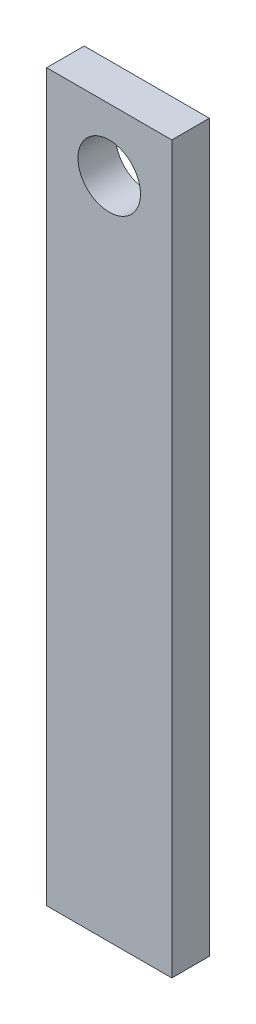
SolidWorks part; units mm, degrees
ref_plane "前基準面" through (0, 0, 0) normal (0, 0, 1) x (1, 0, 0)
ref_plane "上基準面" through (0, 0, 0) normal (0, 1, 0) x (1, 0, 0)
ref_plane "右基準面" through (0, 0, 0) normal (1, 0, 0) x (0, 0, -1)
sketch "草圖1" plane through (0, 0, 0) normal (0, 0, 1) x (1, 0, 0)
  line L0 (0, 29) -> (0, -29) construction
  line L1 (-5, -29) -> (5, -29)
  line L2 (-5, -29) -> (-5, 29)
  line L3 (-5, 29) -> (5, 29)
  line L4 (5, -29) -> (5, 29)
  line L5 (-5, -29) -> (5, 29) construction
  line L6 (-5, 29) -> (5, -29) construction
  circle A0 centre (0, 24) radius 2.5
  point P0 (0, 0)
  point P10 (0, 23.9945)
  dimension "D4" = 5
  dimension "D1" = 10
  dimension "D2" = 58
  dimension "D3" = 53
extrude "填料-伸長1" add sketch "草圖1" along normal blind 3
